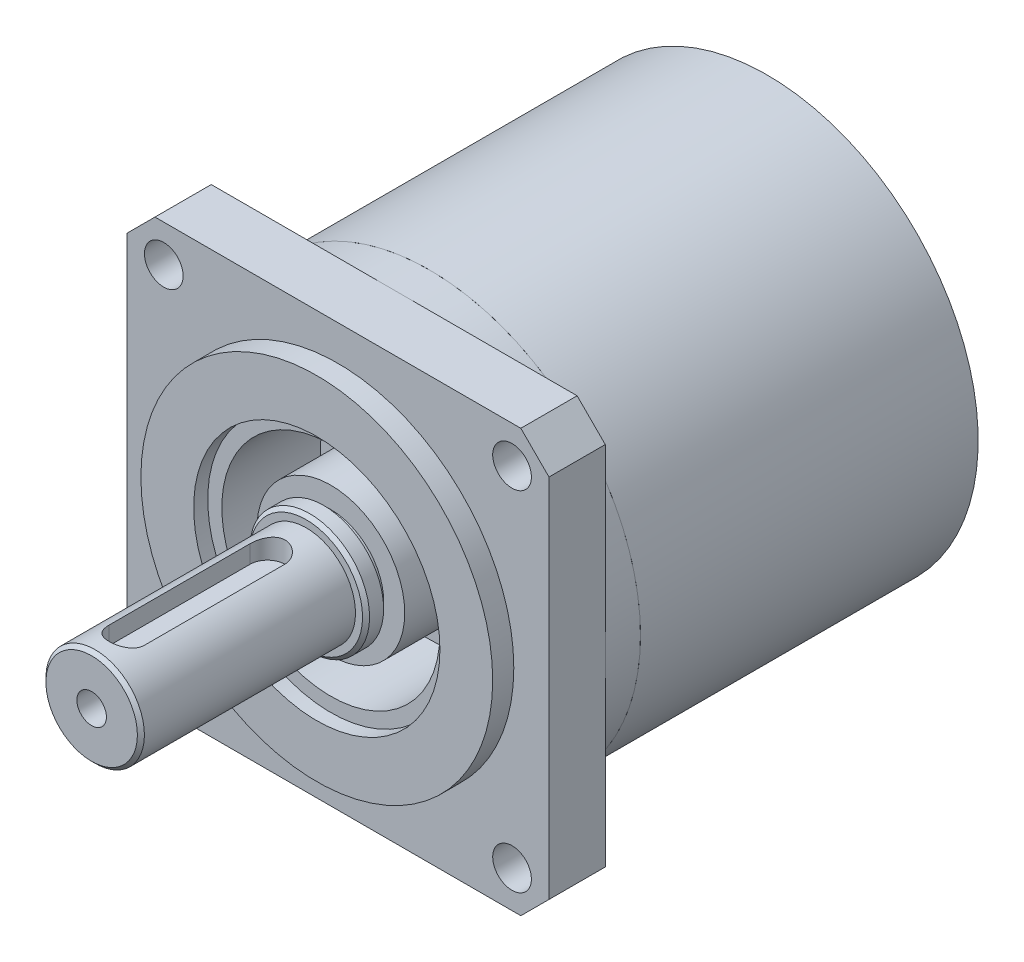
SolidWorks part; units mm, degrees
ref_plane "前视基准面" through (0, 0, 0) normal (0, 0, 1) x (1, 0, 0)
ref_plane "上视基准面" through (0, 0, 0) normal (0, 1, 0) x (1, 0, 0)
ref_plane "右视基准面" through (0, 0, 0) normal (1, 0, 0) x (0, 0, -1)
sketch "草图1" plane through (0, 0, 0) normal (0, 0, 1) x (1, 0, 0)
  circle A0 centre (0, 0) radius 30
  dimension "D1" = 60
extrude "凸台-拉伸1" add sketch "草图1" along normal blind 13
sketch "草图2" plane through (0, 0, 0) normal (0, 0, -1) x (-1, 0, 0)
  circle A0 centre (0, 0) radius 30
extrude "凸台-拉伸2" add sketch "草图2" along normal blind 48 separate body
sketch "草图3" plane through (0, 0, 13) normal (0, 0, 1) x (1, 0, 0)
  circle A0 centre (0, 0) radius 25
  circle A1 centre (0, 0) radius 17.5
  dimension "D1" = 35
  dimension "D2" = 50
extrude "凸台-拉伸3" add sketch "草图3" along normal blind 3
sketch "草图4" plane through (0, 0, 13) normal (0, 0, 1) x (1, 0, 0)
  circle A0 centre (0, 0) radius 17.5
  dimension "D1" = 35
extrude "切除-拉伸1" cut sketch "草图4" against normal blind 13
sketch "草图6" plane through (0, 0, 0) normal (0, 0, 1) x (1, 0, 0)
  circle A0 centre (0, 0) radius 15.5
  circle A1 centre (0, 0) radius 17.5
  dimension "D1" = 35
  dimension "D2" = 31
extrude "凸台-拉伸4" add sketch "草图6" along normal blind 14 separate body
sketch "草图7" plane through (0, 0, 0) normal (0, 0, 1) x (1, 0, 0)
  circle A0 centre (0, 0) radius 10.5
  dimension "D1" = 21
extrude "凸台-拉伸5" add sketch "草图7" along normal blind 14 separate body
sketch "草图8" plane through (0, 0, 14) normal (0, 0, 1) x (1, 0, 0)
  circle A0 centre (0, 0) radius 8.5
  dimension "D1" = 17
extrude "凸台-拉伸6" add sketch "草图8" along normal blind 3.5
sketch "草图9" plane through (0, 0, 17.5) normal (0, 0, 1) x (1, 0, 0)
  circle A0 centre (0, 0) radius 7
  dimension "D1" = 14
extrude "凸台-拉伸7" add sketch "草图9" along normal blind 30.5
chamfer "倒角1" distance 0.5 angle 45 2 edges at (7, 0, 48) (8.5, 0, 17.5)
sketch "草图10" plane through (0, 0, 14) normal (0, 0, 1) x (1, 0, 0)
  circle A0 centre (0, 0) radius 7.5
  circle A1 centre (0, 0) radius 15.5
  dimension "D1" = 15
  dimension "D2" = 31
extrude "切除-拉伸7" cut sketch "草图10" along normal blind 1
ref_plane "基准面1" through (0, 4, 0) normal (0, 1, 0) x (1, 0, 0)
sketch "草图11" plane through (0, 4, 0) normal (0, 1, 0) x (1, 0, 0)
  line L0 (0, -23) -> (0, -43) construction
  line L1 (2.5, -23) -> (2.5, -43)
  line L2 (-2.5, -23) -> (-2.5, -43)
  line L3 (-6.5, -48) -> (6.5, -48) construction
  arc A0 (2.5, -23) -> (-2.5, -23) centre (0, -23) ccw
  arc A1 (-2.5, -43) -> (2.5, -43) centre (0, -43) ccw
  point P3 (0, -33)
  dimension "D1" = 5
  dimension "D2" = 20
  dimension "D3" = 5
extrude "切除-拉伸8" cut sketch "草图11" along normal blind 10
hole_wizard "M5 螺纹孔1" positions "草图13" profile "草图12" tap size "M5" standard "Gb"
sketch "草图13" plane through (0, 0, 48) normal (0, 0, 1) x (1, 0, 0)
  point P0 (0, 0)
sketch "草图12" plane through (0, 0, 48) normal (1, 0, 0) x (0, -1, 0)
  line L0 (0, 0) -> (0, 17.2618)
  line L1 (0, 17.2618) -> (2.1, 16)
  line L2 (2.1, 16) -> (2.1, 0)
  line L5 (2.1, 0) -> (0, 0)
  line L10 (0, 17.2618) -> (-2.1, 16) construction
  line L11 (0, -6.35) -> (0, 107.95) construction
  dimension "螺纹孔钻头直径" = 4.2
  dimension "螺纹孔钻头深度" = 16
  dimension "导头角度" = 118
cosmetic thread "孔螺蚊线1" parameters "D1"=12, "D2"=5
sketch "草图14" plane through (0, 0, 13) normal (0, 0, 1) x (1, 0, 0)
  line L0 (0, 0) -> (30, 0) construction
  line L1 (0, 0) -> (21.2132, 21.2132) construction
  circle A0 centre (0, 0) radius 30 construction
  circle A1 centre (0, 0) radius 26
  dimension "D2" = 52
  dimension "D1" = 45
sketch "草图17" plane through (0, 0, 13) normal (0, 0, 1) x (1, 0, 0)
  line L0 (0, 0) -> (-24.1413, -24.1413) construction
  line L1 (0, 0) -> (22.0156, -22.0156) construction
  line L2 (0, 0) -> (-26.7804, 26.7804) construction
  line L3 (0, 0) -> (30, 0) construction
  dimension "D1" = 45
  dimension "D2" = 90
sketch "草图18" plane through (0, 0, 13) normal (0, 0, 1) x (1, 0, 0)
  line L0 (26, 30) -> (30, 26)
  line L1 (-26, -30) -> (26, -30)
  line L2 (-30, -26) -> (-30, 26)
  line L3 (-26, 30) -> (26, 30)
  line L4 (30, -26) -> (30, 26)
  line L5 (-30, -30) -> (30, 30) construction
  line L6 (-30, 30) -> (30, -30) construction
  line L7 (-30, 26) -> (-26, 30)
  line L8 (-26, -30) -> (-30, -26)
  line L9 (26, -30) -> (30, -26)
  point P0 (0, 0)
  dimension "D1" = 60
  dimension "D2" = 60
extrude "凸台-拉伸8" add sketch "草图18" against normal blind 8
sketch "草图19" plane through (0, 0, 13) normal (0, 0, 1) x (1, 0, 0)
  line L0 (0, 0) -> (37.9113, 0) construction
  line L1 (0, 0) -> (30.5688, 30.5688) construction
  circle A0 centre (0, 0) radius 35
  circle A1 centre (24.7487, 24.7487) radius 2.75
  dimension "D1" = 70
  dimension "D3" = 5.5
  dimension "D2" = 45
extrude "切除-拉伸9" cut sketch "草图19" against normal blind 8 contours A0 A1 | A0 A1
pattern_circular "阵列(圆周)1" count 4 over 360 about axis through (0, 0, 0) along (0, 0, 1) of "切除-拉伸9"
sketch "草图20" plane through (0, 0, 13) normal (0, 0, 1) x (1, 0, 0)
  circle A0 centre (0, 0) radius 15.5
sketch "草图21" plane through (0, 0, 13) normal (0, 0, 1) x (1, 0, 0)
  circle A0 centre (0, 0) radius 15.5
  circle A1 centre (0, 0) radius 10.5
  dimension "D1" = 31
  dimension "D2" = 21
extrude "切除-拉伸11" cut sketch "草图21" against normal blind 8
